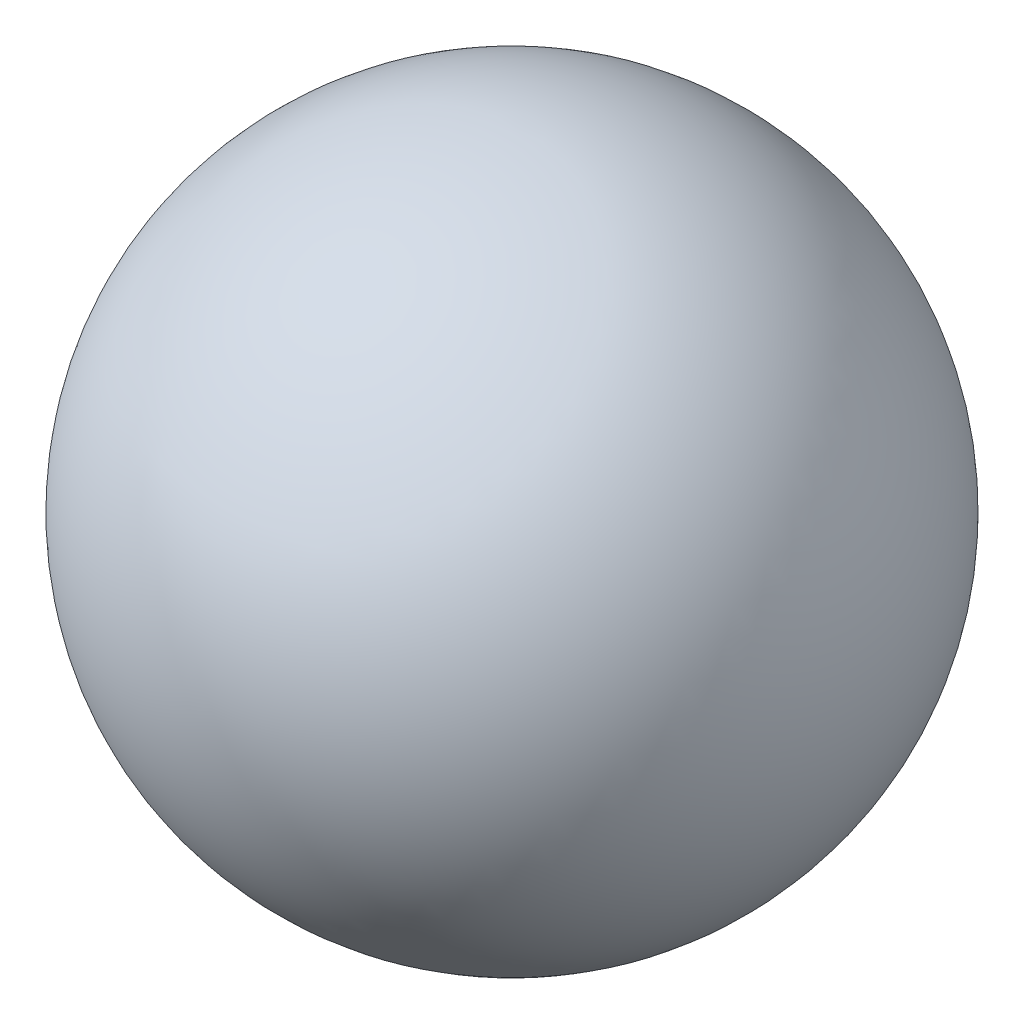
SolidWorks part; units mm, degrees
ref_plane "Front Plane" through (0, 0, 0) normal (0, 0, 1) x (1, 0, 0)
ref_plane "Top Plane" through (0, 0, 0) normal (0, 1, 0) x (1, 0, 0)
ref_plane "Right Plane" through (0, 0, 0) normal (1, 0, 0) x (0, 0, -1)
sketch "Sketch2" plane through (0, 0, 0) normal (0, 0, 1) x (1, 0, 0)
  line L0 (0, -20) -> (0, 20)
  arc A0 (0, -20) -> (0, 20) centre (0, 0) ccw
  dimension "D1" = 40
revolve "Revolve1" add sketch "Sketch2" angle 360 about L0
sketch "Sketch3" plane through (0, 0, 0) normal (0, 1, 0) x (1, 0, 0)
  circle A0 centre (0, 0) radius 6
  dimension "D1" = 12
extrude "Cut-Extrude1" cut sketch "Sketch3" against normal blind 25
